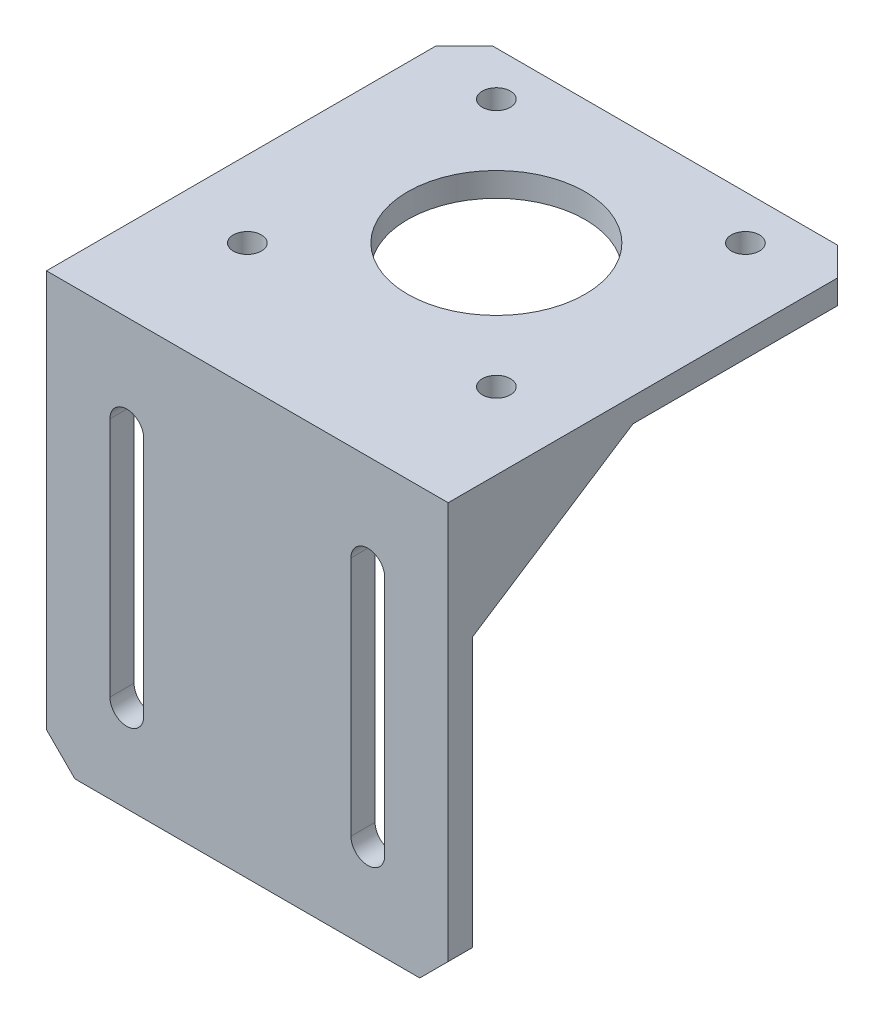
SolidWorks part; units mm, degrees
ref_plane "前视基准面" through (0, 0, 0) normal (0, 0, 1) x (1, 0, 0)
ref_plane "上视基准面" through (0, 0, 0) normal (0, 1, 0) x (1, 0, 0)
ref_plane "右视基准面" through (0, 0, 0) normal (1, 0, 0) x (0, 0, -1)
sketch "草图1" plane through (0, 0, 0) normal (0, 1, 0) x (1, 0, 0)
  line L0 (0, 0) -> (0, 45.4645)
  line L1 (0, 45.4645) -> (3.5355, 49)
  line L2 (3.5355, 49) -> (46.4645, 49)
  line L3 (46.4645, 49) -> (50, 45.4645)
  line L4 (50, 45.4645) -> (50, 0)
  line L5 (50, 0) -> (0, 0)
  line L6 (25, 49) -> (25, 7) construction
  circle A0 centre (25, 28) radius 11.05
  circle A1 centre (9.5, 12.5) radius 1.75
  circle A2 centre (9.5, 43.5) radius 1.75
  circle A3 centre (40.5, 43.5) radius 1.75
  circle A4 centre (40.5, 12.5) radius 1.75
  point P7 (25, 25.5592)
  point P20 (25, 28)
  point P22 (25.3237, 23.3925)
  dimension "D3" = 22.1
  dimension "D4" = 3.5
  dimension "D5" = 31
  dimension "D10" = 21
  dimension "D2" = 50
  dimension "D6" = 49
  dimension "D7" = 45
  dimension "D8" = 45
  dimension "D9" = 5
  dimension "D1" = 4
extrude "凸台-拉伸1" add sketch "草图1" along normal blind 3
sketch "草图2" plane through (0, 0, 0) normal (0, 0, 1) x (1, 0, 0)
  line L0 (0, 3) -> (0, -46.4645)
  line L1 (0, -46.4645) -> (3.5355, -50)
  line L2 (3.5355, -50) -> (46.4645, -50)
  line L3 (46.4645, -50) -> (50, -46.4645)
  line L4 (50, -46.4645) -> (50, 3)
  line L5 (50, 3) -> (0, 3)
  line L6 (10, -9) -> (10, -39) construction
  line L7 (12.1, -9) -> (12.1, -39)
  line L8 (7.9, -9) -> (7.9, -39)
  line L9 (25, 3) -> (25, -47.9163) construction
  line L10 (40, -9) -> (40, -39) construction
  line L11 (37.9, -9) -> (37.9, -39)
  line L12 (42.1, -9) -> (42.1, -39)
  arc A0 (12.1, -9) -> (7.9, -9) centre (10, -9) ccw
  arc A1 (7.9, -39) -> (12.1, -39) centre (10, -39) ccw
  arc A2 (37.9, -9) -> (42.1, -9) centre (40, -9) cw
  arc A3 (42.1, -39) -> (37.9, -39) centre (40, -39) cw
  point P11 (10, -24)
  point P20 (40, -24)
  dimension "D1" = 45
  dimension "D2" = 45
  dimension "D3" = 53
  dimension "D4" = 5
  dimension "D5" = 4.2
  dimension "D6" = 30
  dimension "D7" = 11
  dimension "D8" = 30
extrude "凸台-拉伸2" add sketch "草图2" along normal blind 3
sketch "草图3" plane through (50, 0, 0) normal (1, 0, 0) x (0, 0, -1)
  line L0 (0, 0) -> (0, -13)
  line L1 (0, -46.4645) -> (0, 0) construction
  line L2 (0, -13) -> (20, 0)
  line L3 (0, 0) -> (45.4645, 0) construction
  line L4 (20, 0) -> (0, 0)
  dimension "D1" = 20
  dimension "D2" = 13
extrude "凸台-拉伸3" add sketch "草图3" against normal blind 3
sketch "草图4" plane through (0, 0, 0) normal (-1, 0, 0) x (0, 0, 1)
  line L0 (-20, 0) -> (0, 0)
  line L1 (0, 0) -> (0, -13)
  line L2 (0, -13) -> (-20, 0)
extrude "凸台-拉伸4" add sketch "草图4" against normal blind 3
